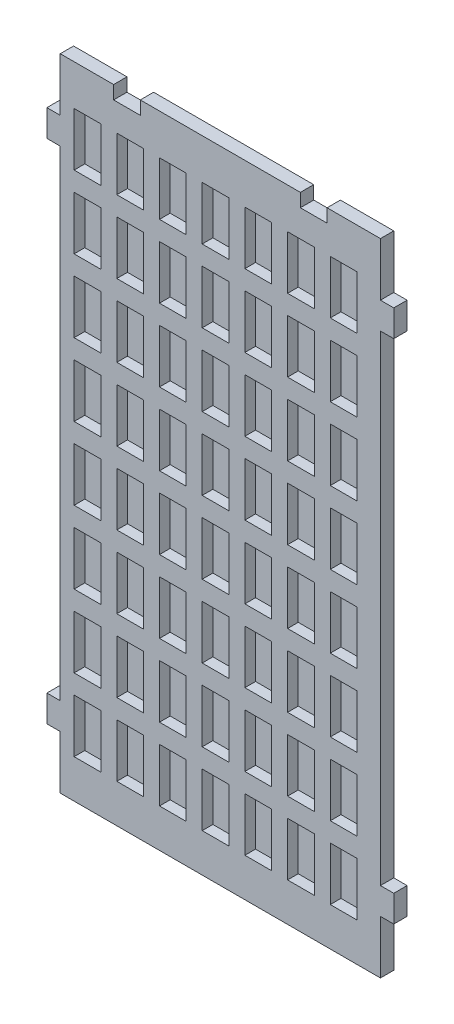
SolidWorks part; units mm, degrees
ref_plane "Front Plane" through (0, 0, 0) normal (0, 0, 1) x (1, 0, 0)
ref_plane "Top Plane" through (0, 0, 0) normal (0, 1, 0) x (1, 0, 0)
ref_plane "Right Plane" through (0, 0, 0) normal (1, 0, 0) x (0, 0, -1)
sketch "Sketch1" plane through (0, 0, 0) normal (0, 0, 1) x (1, 0, 0)
  line L0 (19.05, 0) -> (57.15, 0)
  line L1 (0, 0) -> (12.7, 0)
  line L2 (0, 0) -> (0, -12.7)
  line L3 (0, -152.4) -> (12.7, -152.4)
  line L4 (76.2, -19.05) -> (76.2, -133.35)
  line L5 (63.5, 0) -> (76.2, 0)
  line L6 (12.7, 0) -> (12.7, -3.175)
  line L7 (12.7, -3.175) -> (19.05, -3.175)
  line L8 (19.05, 0) -> (19.05, -3.175)
  line L9 (0, -19.05) -> (0, -133.35)
  line L10 (57.15, 0) -> (57.15, -3.175)
  line L11 (57.15, -3.175) -> (63.5, -3.175)
  line L12 (63.5, 0) -> (63.5, -3.175)
  line L13 (76.2, -12.7) -> (79.375, -12.7)
  line L14 (76.2, -139.7) -> (76.2, -152.4)
  line L15 (76.2, -19.05) -> (79.375, -19.05)
  line L16 (79.375, -12.7) -> (79.375, -19.05)
  line L17 (76.2, -133.35) -> (79.375, -133.35)
  line L18 (63.5, -152.4) -> (76.2, -152.4)
  line L19 (76.2, -139.7) -> (79.375, -139.7)
  line L20 (79.375, -133.35) -> (79.375, -139.7)
  line L21 (12.7, -152.4) -> (63.5, -152.4)
  line L25 (0, -139.7) -> (0, -152.4)
  line L29 (0, -139.7) -> (-3.175, -139.7)
  line L31 (0, -133.35) -> (-3.175, -133.35)
  line L32 (-3.175, -139.7) -> (-3.175, -133.35)
  line L33 (0, -19.05) -> (-3.175, -19.05)
  line L34 (76.2, 0) -> (76.2, -12.7)
  line L35 (0, -12.7) -> (-3.175, -12.7)
  line L36 (-3.175, -19.05) -> (-3.175, -12.7)
  dimension "D3" = 12.7
  dimension "D4" = 6.35
  dimension "D5" = 3.175
  dimension "D6" = 6.35
  dimension "D7" = 3.175
  dimension "D8" = 12.7
  dimension "D9" = 152.4
  dimension "D10" = 6.35
  dimension "D11" = 3.175
  dimension "D12" = 3.175
  dimension "D13" = 6.35
  dimension "D14" = 12.7
  dimension "D15" = 76.2
  dimension "D21" = 3.175
  dimension "D22" = 6.35
  dimension "D23" = 12.7
  dimension "D24" = 12.7
  dimension "D25" = 6.35
  dimension "D26" = 3.175
  dimension "D27" = 3.175
  dimension "D29" = 3.175
  dimension "D30" = 12.7
extrude "Boss-Extrude1" add sketch "Sketch1" along normal blind 3.175
sketch "Sketch2" plane through (0, 0, 3.175) normal (0, 0, 1) x (1, 0, 0)
  line L0 (12.7, -3.175) -> (19.05, -3.175) construction
  line L1 (3.302, -9.6314) -> (9.652, -9.6314)
  line L2 (3.302, -9.6314) -> (3.302, -22.3314)
  line L3 (3.302, -22.3314) -> (9.652, -22.3314)
  line L4 (9.652, -9.6314) -> (9.652, -22.3314)
  line L5 (3.302, -9.6314) -> (9.652, -22.3314) construction
  line L6 (3.302, -22.3314) -> (9.652, -9.6314) construction
  line L7 (0, -19.05) -> (0, -133.35) construction
  point P0 (6.477, -15.9814)
  dimension "D1" = 6.4564
  dimension "D2" = 6.35
  dimension "D3" = 12.7
  dimension "D4" = 3.302
extrude "Cut-Extrude1" cut sketch "Sketch2" against normal blind 2.54
pattern_linear "LPattern1" count 7 spacing 10.16 along (1, 0, 0) count 8 spacing 17.272 along (0, -1, 0) of "Cut-Extrude1"
